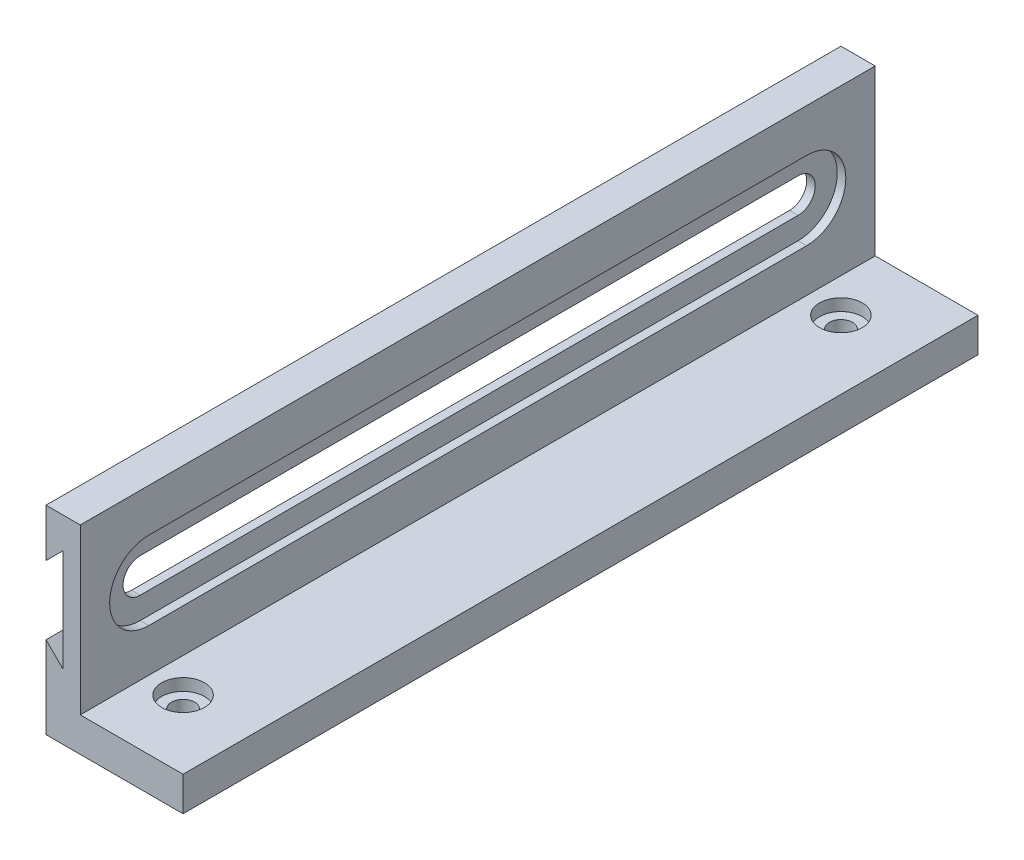
SolidWorks part; units mm, degrees
ref_plane "Front Plane" through (0, 0, 0) normal (0, 0, 1) x (1, 0, 0)
ref_plane "Top Plane" through (0, 0, 0) normal (0, 1, 0) x (1, 0, 0)
ref_plane "Right Plane" through (0, 0, 0) normal (1, 0, 0) x (0, 0, -1)
sketch "Sketch1" plane through (0, 0, 0) normal (0, 1, 0) x (1, 0, 0)
  line L1 (0, 0) -> (25.4, 0)
  line L2 (0, 0) -> (0, 147.32)
  line L3 (0, 147.32) -> (25.4, 147.32)
  line L4 (25.4, 0) -> (25.4, 147.32)
  dimension "D1" = 147.32
  dimension "D2" = 25.4
extrude "Boss-Extrude1" add sketch "Sketch1" against normal blind 6.35
sketch "Sketch2" plane through (0, 0, 0) normal (-1, 0, 0) x (0, 0, 1)
  line L1 (0, 0) -> (-147.32, 0)
  line L2 (0, 0) -> (0, 30.48)
  line L3 (0, 30.48) -> (-147.32, 30.48)
  line L4 (-147.32, 0) -> (-147.32, 30.48)
  line L5 (-147.32, -6.35) -> (-147.32, 0) construction
  dimension "D1" = 30.48
extrude "Boss-Extrude2" add sketch "Sketch2" against normal blind 6.35
sketch "Sketch5" plane through (0, 0, 0) normal (0, 1, 0) x (1, 0, 0)
  line L0 (12.7, 0) -> (12.7, 147.32)
  line L1 (6.35, 0) -> (25.4, 0) construction
  line L2 (25.4, 147.32) -> (6.35, 147.32) construction
  line L3 (0, 0) -> (25.4, 0) construction
  point P9 (12.7, 12.7)
  point P11 (12.7, 134.62)
  dimension "D1" = 12.7
  dimension "D2" = 121.92
hole_wizard "CBORE for #6 Binding Head Machine Screw1" positions "Sketch7" profile "Sketch8" counterbore size "#6" standard "ANSI Inch" end condition up to next
sketch "Sketch7" plane through (0, 0, 0) normal (0, 1, 0) x (1, 0, 0)
  point P0 (12.7, 12.7)
  point P3 (12.7, 134.62)
sketch "Sketch8" plane through (12.7, 0, -12.7) normal (1, 0, 0) x (0, 0, 1)
  line L0 (0, 0) -> (0, 6.35)
  line L1 (0, 6.35) -> (2.1526, 6.35)
  line L3 (2.1526, 6.35) -> (2.1527, 2.2098)
  line L4 (2.1527, 2.2098) -> (3.9687, 2.2098)
  line L5 (3.9687, 2.2098) -> (3.9687, 0)
  line L7 (3.9687, 0) -> (0, 0)
  line L11 (0, -6.35) -> (0, 107.95) construction
  dimension "Thru Hole Dia." = 4.3053
  dimension "Thru Hole Depth" = 6.35
  dimension "C'Bore Dia." = 7.9375
  dimension "C'Bore Depth" = 2.2098
sketch "Sketch9" plane through (6.35, 0, 0) normal (1, 0, 0) x (0, 0, -1)
  line L1 (12.7, 15.24) -> (134.62, 15.24) construction
  line L4 (12.7, 18.415) -> (134.62, 18.415)
  line L9 (12.7, 12.065) -> (134.62, 12.065)
  arc A2 (12.7, 18.415) -> (12.7, 12.065) centre (12.7, 15.24) ccw
  arc A3 (134.62, 12.065) -> (134.62, 18.415) centre (134.62, 15.24) ccw
  point P17 (73.66, 15.24)
extrude "Cut-Extrude1" cut sketch "Sketch9" against normal through all contours L4 A3 L9 A2
sketch "Sketch12" plane through (6.35, 0, 0) normal (1, 0, 0) x (0, 0, -1)
  line L0 (12.7, 15.24) -> (134.62, 15.24) construction
  line L1 (12.7, 22.4937) -> (134.62, 22.4937)
  line L2 (12.7, 7.9863) -> (134.62, 7.9863)
  arc A0 (12.7, 22.4937) -> (12.7, 7.9863) centre (12.7, 15.24) ccw
  arc A1 (134.62, 7.9863) -> (134.62, 22.4937) centre (134.62, 15.24) ccw
  point P4 (73.66, 15.24)
  dimension "D1" = 7.2537
extrude "Cut-Extrude2" cut sketch "Sketch12" against normal blind 1.5875
sketch "Sketch13" plane through (0, 0, -147.32) normal (0, 0, -1) x (-1, 0, 0)
  line L0 (-3.175, 15.24) -> (-6.35, 15.24)
  line L2 (0, 21.59) -> (0, 8.89)
  line L4 (-3.175, 24.765) -> (-3.175, 5.715)
  line L5 (-6.35, 30.48) -> (-6.35, 0) construction
  line L8 (-3.175, 24.765) -> (0, 21.59)
  line L9 (-3.175, 5.715) -> (0, 8.89)
  line L11 (0, -6.35) -> (0, 30.48) construction
  line L18 (-6.35, 0) -> (-25.4, 0)
  line L19 (-25.4, 0) -> (-25.4, -6.35)
  line L20 (-25.4, -6.35) -> (0, -6.35)
  line L21 (0, -6.35) -> (0, 30.48)
  line L22 (0, 30.48) -> (-6.35, 30.48)
  line L23 (-6.35, 30.48) -> (-6.35, 0)
  line L24 (-6.35, 0) -> (-25.4, 0)
  line L25 (-25.4, 0) -> (-25.4, -6.35)
  line L26 (-25.4, -6.35) -> (0, -6.35)
  line L27 (0, 8.89) -> (0, 30.48)
  dimension "D1" = 3.175
  dimension "D2" = 12.7
  dimension "D3" = 45
  dimension "D4" = 45
  dimension "D5" = 0
extrude "Cut-Extrude3" cut sketch "Sketch13" against normal through all contours L4 L8 L2 L9
ref_plane "Plane1" through (6.35, 0, 0) normal (0, 0, 1) x (1, 0, 0)
